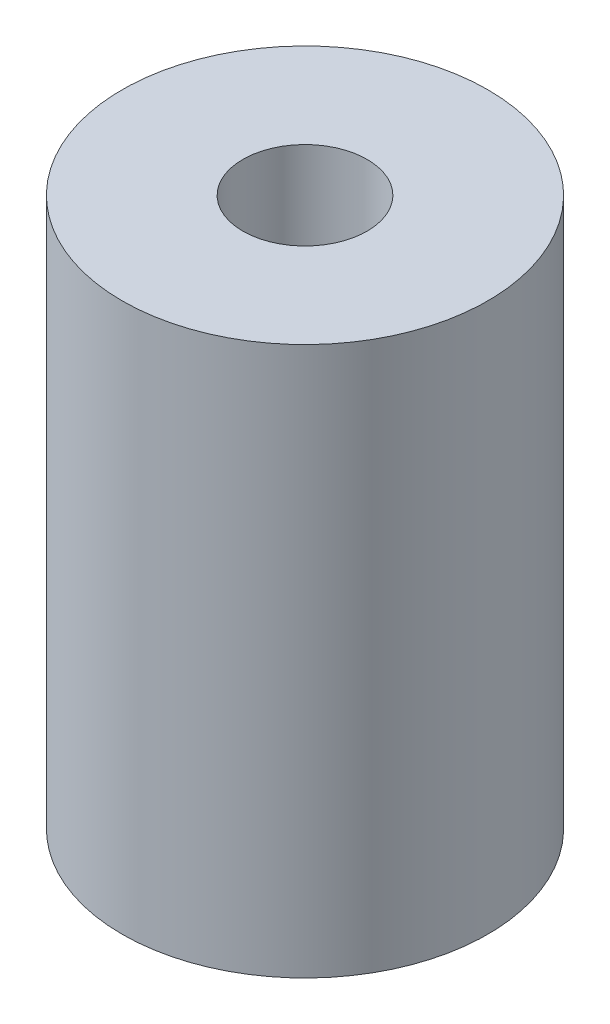
SolidWorks part; units mm, degrees
ref_plane "前视基准面" through (0, 0, 0) normal (0, 0, 1) x (1, 0, 0)
ref_plane "上视基准面" through (0, 0, 0) normal (0, 1, 0) x (1, 0, 0)
ref_plane "右视基准面" through (0, 0, 0) normal (1, 0, 0) x (0, 0, -1)
sketch "草图1" plane through (0, 0, 0) normal (0, 1, 0) x (1, 0, 0)
  circle A0 centre (0, 0) radius 1.7
  circle A1 centre (0, 0) radius 5
  dimension "D1" = 3.4
  dimension "D2" = 10
extrude "凸台-拉伸1" add sketch "草图1" along normal blind 15
